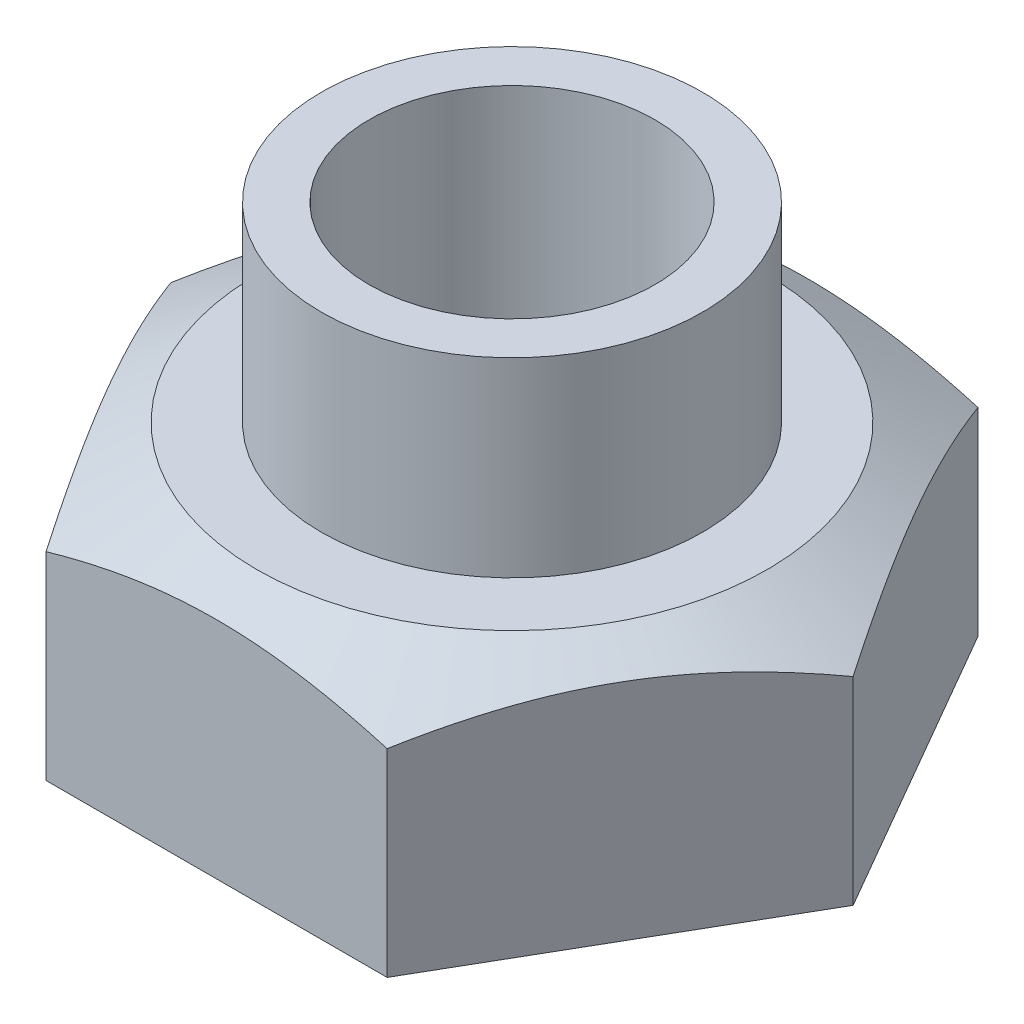
SolidWorks part; units mm, degrees
ref_plane "Front Plane" through (0, 0, 0) normal (0, 0, 1) x (1, 0, 0)
ref_plane "Top Plane" through (0, 0, 0) normal (0, 1, 0) x (1, 0, 0)
ref_plane "Right Plane" through (0, 0, 0) normal (1, 0, 0) x (0, 0, -1)
sketch "Sketch1" plane through (0, 0, 0) normal (0, 1, 0) x (1, 0, 0)
  line L1 (44.7446, -77.5) -> (89.4893, 0)
  line L2 (89.4893, 0) -> (44.7446, 77.5)
  line L3 (44.7446, 77.5) -> (-44.7446, 77.5)
  line L4 (-44.7446, 77.5) -> (-89.4893, 0)
  line L5 (-89.4893, 0) -> (-44.7446, -77.5)
  line L6 (-44.7446, -77.5) -> (44.7446, -77.5)
  circle A0 centre (0, 0) radius 77.5 construction
  dimension "D1" = 155
extrude "Boss-Extrude1" add sketch "Sketch1" along normal blind 65
ref_plane "Plane1" through (0, 0, 0) normal (0, 0, 1) x (1, 0, 0)
sketch "Sketch5" plane through (0, 0, 0) normal (0, 0, 1) x (1, 0, 0)
  line L0 (0, 80.5443) -> (0, -35.2383) construction
  line L1 (66.9462, 65) -> (89.4893, 65)
  line L2 (44.7446, 65) -> (89.4893, 65) construction
  line L3 (89.4893, 65) -> (89.4893, 51.9847)
  line L4 (89.4893, 65) -> (89.4893, 0) construction
  line L5 (89.4893, 51.9847) -> (66.9462, 65)
  dimension "D1" = 13.0153
  dimension "D2" = 60
revolve "Cut-Revolve1" cut sketch "Sketch5" angle 360 about L0
sketch "Sketch7" plane through (0, 65, 0) normal (0, 1, 0) x (1, 0, 0)
  circle A0 centre (0, 0) radius 50
  dimension "D1" = 100
extrude "Boss-Extrude2" add sketch "Sketch7" along normal blind 50
sketch "Sketch8" plane through (0, 115, 0) normal (0, 1, 0) x (1, 0, 0)
  circle A0 centre (0, 0) radius 37.5
  dimension "D1" = 75
extrude "Cut-Extrude1" cut sketch "Sketch8" against normal through all
